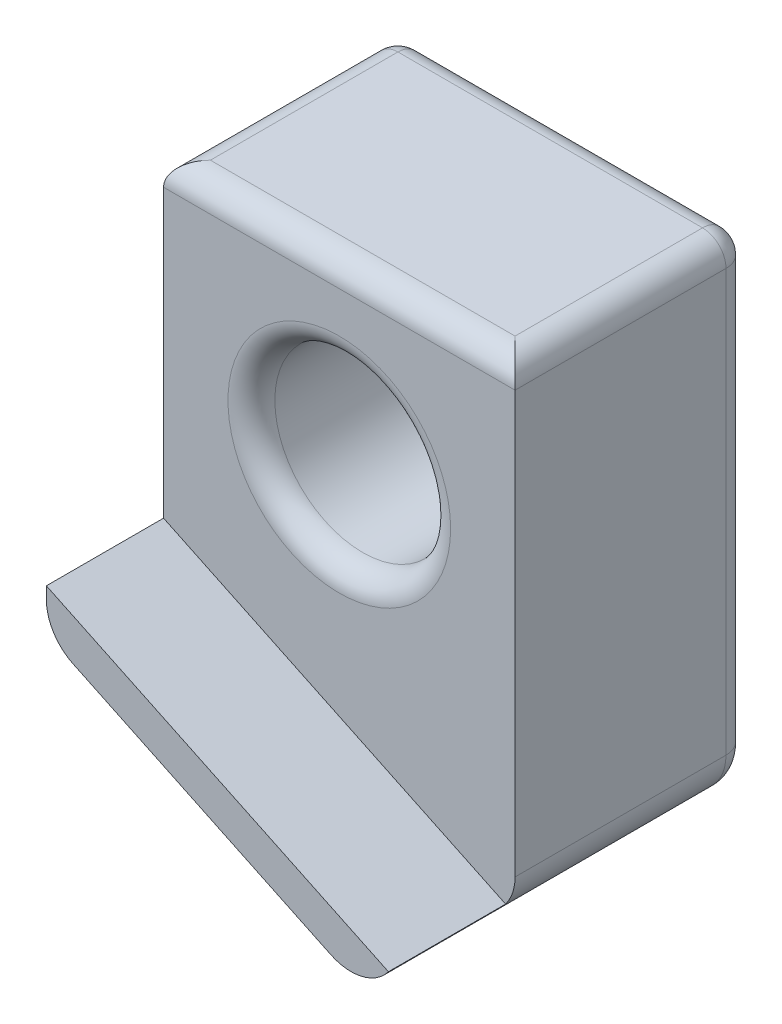
SolidWorks part; units mm, degrees
ref_plane "Front Plane" through (0, 0, 0) normal (0, 0, 1) x (1, 0, 0)
ref_plane "Top Plane" through (0, 0, 0) normal (0, 1, 0) x (1, 0, 0)
ref_plane "Right Plane" through (0, 0, 0) normal (1, 0, 0) x (0, 0, -1)
sketch "Sketch1" plane through (0, 0, 0) normal (0, 0, 1) x (1, 0, 0)
  line L0 (-7.5, 0) -> (-7.5, 7.5)
  line L1 (2.0352, 3.525) -> (-2.0352, 3.525) construction
  line L2 (-2.0352, 3.525) -> (-4.0703, 0) construction
  line L3 (-4.0703, 0) -> (-2.0352, -3.525) construction
  line L4 (-2.0352, -3.525) -> (2.0352, -3.525) construction
  line L5 (2.0352, -3.525) -> (4.0703, 0) construction
  line L6 (4.0703, 0) -> (2.0352, 3.525) construction
  line L7 (-7.5, 7.5) -> (7.5, 7.5)
  line L8 (7.5, 7.5) -> (7.5, 0)
  circle A0 centre (0, 0) radius 3.525 construction
  circle A1 centre (0, 0) radius 3.75
  arc A2 (-7.5, 0) -> (7.5, 0) centre (0, 0) ccw
  dimension "D2" = 7.5
  dimension "D3" = 7.5
  dimension "D1" = 7.05
  dimension "D4" = 15
extrude "Boss-Extrude1" add sketch "Sketch1" along normal blind 10
sketch "Sketch2" plane through (0, 0, 0) normal (0, 0, -1) x (-1, 0, 0)
  line L0 (-7.5, 0) -> (-7.5, -14.6587)
  line L1 (-7.5, -14.6587) -> (7.5, -7.5014)
  line L2 (7.5, -7.5014) -> (7.5, 0)
  line L3 (7.5, 7.5) -> (7.5, 0) construction
  line L4 (-7.5, 0) -> (-7.5, 7.5) construction
  line L5 (-126.518, -69.2329) -> (43.6074, 11.9435) construction
  arc A0 (7.5, 0) -> (-7.5, 0) centre (0, 0) cw
  dimension "D1" = 2
extrude "Boss-Extrude2" add sketch "Sketch2" against normal through all
sketch "Sketch3" plane through (0, 0, 10) normal (0, 0, 1) x (1, 0, 0)
  line L0 (-7.5, -5.2854) -> (7.5, -12.4427) construction
  line L1 (126.518, -69.2329) -> (-43.6074, 11.9435) construction
  line L2 (-7.5, 7.5) -> (-7.5, -7.5014) construction
  line L3 (7.5, -14.6587) -> (7.5, 7.5) construction
  line L4 (7.5, -12.8859) -> (7.5, -14.6587)
  line L5 (7.5, -14.6587) -> (-7.5, -7.5014)
  line L6 (-7.5, -7.5014) -> (-7.5, -5.7286)
  line L7 (-7.5, -5.7286) -> (7.5, -12.8859)
  dimension "D1" = 0.4
extrude "Boss-Extrude3" add sketch "Sketch3" along normal blind 5
fillet "Fillet1" radius 2 2 edges at (-7.5, -7.5014, 7.5) (7.5, -14.6587, 7.5)
fillet "Fillet2" radius 1 10 edges at (3.75, 0, 10) (7.5, -1.9942, 0) (6.5671, -13.1799, 0) (-7.5, 0.6302, 0) (-7.1915, -7.3068, 0) (0, 7.5, 10) (0, 7.5, 0) (-0.8613, -10.6691, 0) (-7.5, 7.5, 5) (7.5, 7.5, 5)
